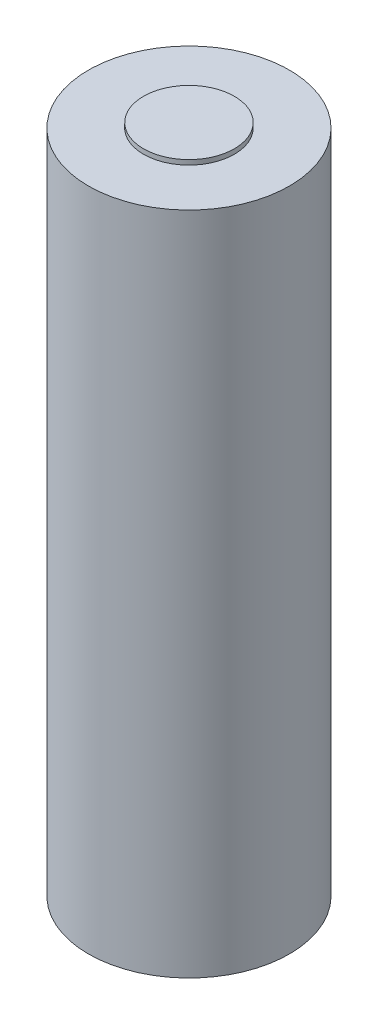
SolidWorks part; units mm, degrees
ref_plane "Front Plane" through (0, 0, 0) normal (0, 0, 1) x (1, 0, 0)
ref_plane "Top Plane" through (0, 0, 0) normal (0, 1, 0) x (1, 0, 0)
ref_plane "Right Plane" through (0, 0, 0) normal (1, 0, 0) x (0, 0, -1)
sketch "Sketch1" plane through (0, 0, 0) normal (0, 1, 0) x (1, 0, 0)
  circle A0 centre (0, 0) radius 10.5
  dimension "D1" = 21
extrude "Boss-Extrude1" add sketch "Sketch1" along normal blind 70
sketch "Sketch2" plane through (0, 70, 0) normal (0, 1, 0) x (1, 0, 0)
  circle A0 centre (0, 0) radius 4.75
  circle A2 centre (0, 0) radius 10.5
  circle A3 centre (0, 0) radius 10.5
  dimension "D1" = 9.5
  dimension "D2" = 0
extrude "Cut-Extrude1" cut sketch "Sketch2" against normal blind 0.5
